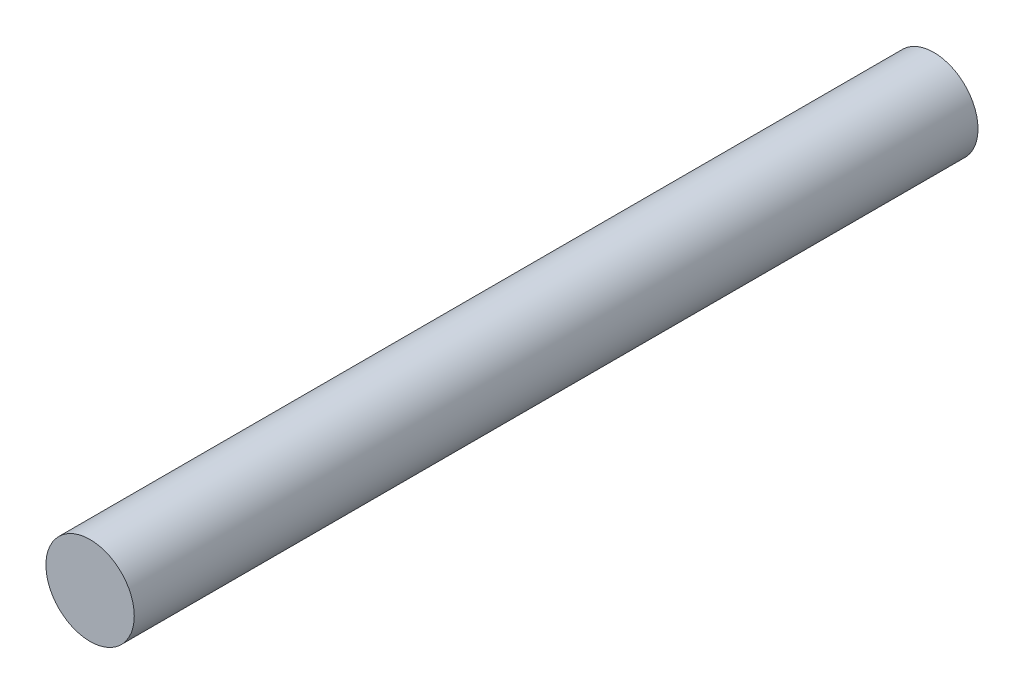
SolidWorks part; units mm, degrees
ref_plane "Front Plane" through (0, 0, 0) normal (0, 0, 1) x (1, 0, 0)
ref_plane "Top Plane" through (0, 0, 0) normal (0, 1, 0) x (1, 0, 0)
ref_plane "Right Plane" through (0, 0, 0) normal (1, 0, 0) x (0, 0, -1)
sketch "Sketch1" plane through (0, 0, 0) normal (0, 0, 1) x (1, 0, 0)
  circle A1 centre (0, 0) radius 5
extrude "Boss-Extrude1" add sketch "Sketch1" against normal up to surface (95.5 mm away)
